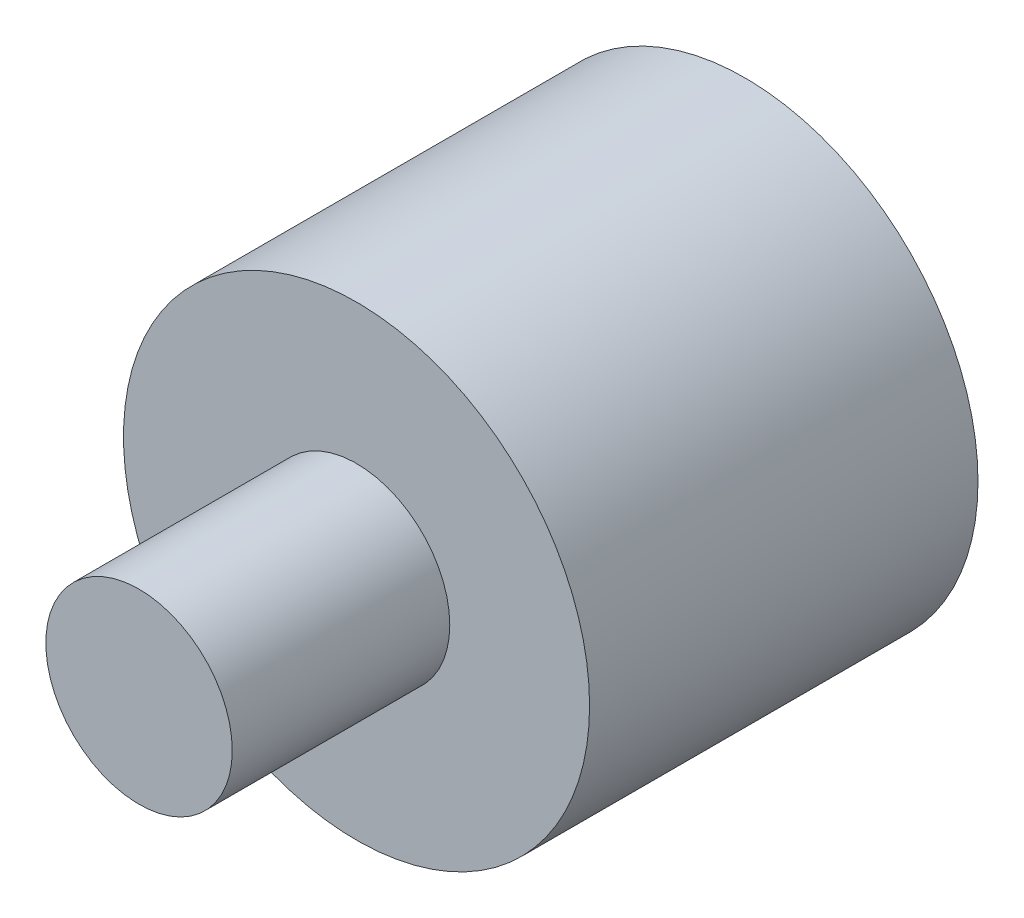
SolidWorks part; units mm, degrees
ref_plane "Front Plane" through (0, 0, 0) normal (0, 0, 1) x (1, 0, 0)
ref_plane "Top Plane" through (0, 0, 0) normal (0, 1, 0) x (1, 0, 0)
ref_plane "Right Plane" through (0, 0, 0) normal (1, 0, 0) x (0, 0, -1)
sketch "Sketch1" plane through (0, 0, 0) normal (0, 0, 1) x (1, 0, 0)
  circle A0 centre (0, 0) radius 7.5
  dimension "D1" = 15
extrude "Boss-Extrude1" add sketch "Sketch1" along normal blind 12.5
sketch "Sketch2" plane through (0, 0, 12.5) normal (0, 0, 1) x (1, 0, 0)
  circle A0 centre (0, 0) radius 3
  dimension "D1" = 6
extrude "Boss-Extrude2" add sketch "Sketch2" along normal blind 7
